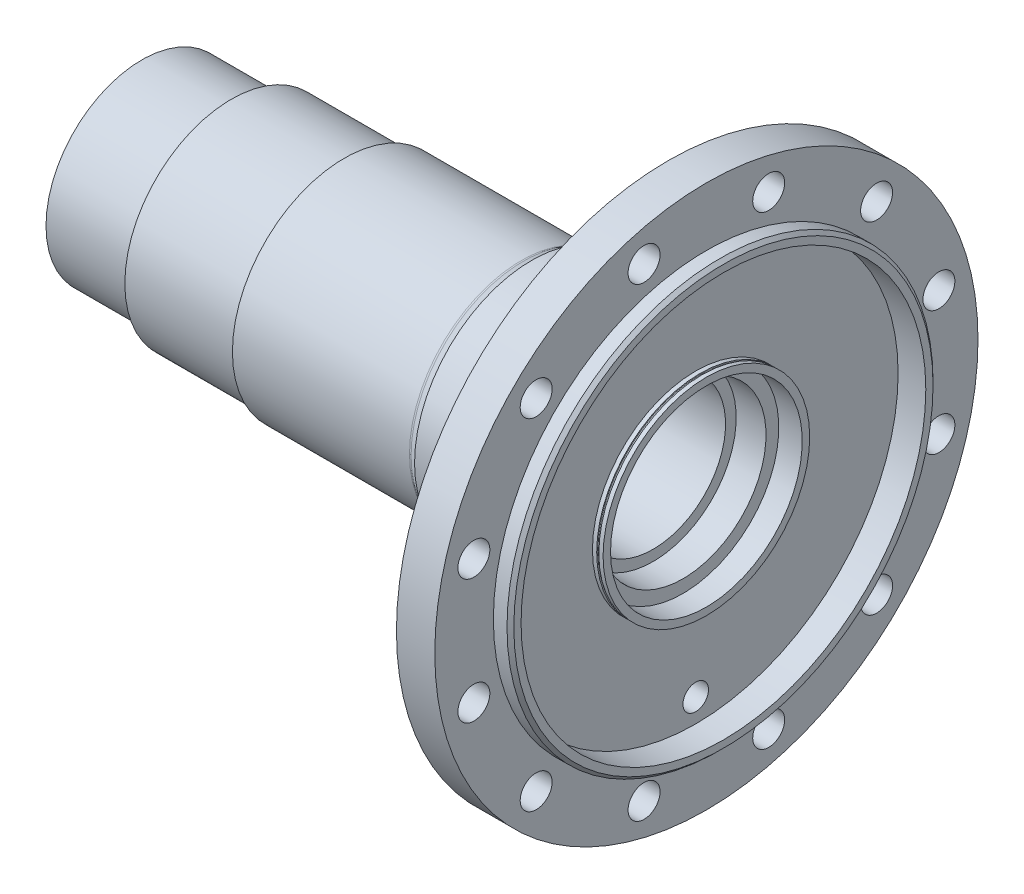
SolidWorks part; units mm, degrees
ref_plane "Спереди" through (0, 0, 0) normal (0, 0, 1) x (1, 0, 0)
ref_plane "Сверху" through (0, 0, 0) normal (0, 1, 0) x (1, 0, 0)
ref_plane "Справа" through (0, 0, 0) normal (1, 0, 0) x (0, 0, -1)
sketch "Эскиз1" plane through (0, 0, 0) normal (0, 0, 1) x (1, 0, 0)
  line L0 (0, 0) -> (273, 0)
  line L1 (0, 0) -> (0, 45)
  line L2 (0, 45) -> (42, 45)
  line L3 (42, 45) -> (42, 50)
  line L4 (42, 50) -> (95, 50)
  line L5 (95, 50) -> (95, 52.5)
  line L6 (95, 52.5) -> (178.134, 52.5)
  line L7 (179.134, 52.7679) -> (183, 55)
  line L8 (183, 55) -> (213, 55)
  line L9 (215, 57) -> (215, 60.7679)
  line L10 (215, 60.7679) -> (218, 62.5)
  line L11 (218, 62.5) -> (237, 62.5)
  line L12 (239, 64.5) -> (239, 100)
  line L13 (239, 100) -> (247, 100)
  line L14 (247, 100) -> (247, 127.5)
  line L15 (247, 127.5) -> (265, 127.5)
  line L16 (265, 127.5) -> (265, 100)
  line L17 (265, 100) -> (271.4, 100)
  line L18 (271.4, 100) -> (273, 98.4)
  line L19 (273, 98.4) -> (273, 0)
  arc A0 (178.134, 52.5) -> (179.134, 52.7679) centre (178.134, 54.5) ccw
  arc A1 (213, 55) -> (215, 57) centre (213, 57) ccw
  arc A2 (237, 62.5) -> (239, 64.5) centre (237, 64.5) ccw
revolve "Повернуть1" add sketch "Эскиз1" angle 360 about L0
sketch "Эскиз2" plane through (0, 0, 0) normal (0, 0, 1) x (1, 0, 0)
  line L0 (0, 0) -> (273, 0)
  line L1 (0, 0) -> (0, 31)
  line L2 (0, 31) -> (203.5, 31)
  line L3 (203.5, 31) -> (203.5, 34)
  line L4 (203.5, 34) -> (240, 34)
  line L5 (240, 34) -> (240, 39)
  line L6 (240, 39) -> (254, 39)
  line L7 (254, 39) -> (254, 45)
  line L8 (254, 45) -> (265, 45)
  line L9 (265, 45) -> (265, 95)
  line L10 (265, 95) -> (273, 95)
  line L11 (273, 95) -> (273, 0)
revolve "Вырез-Повернуть1" cut sketch "Эскиз2" angle 360 about L0
sketch "Эскиз3" plane through (0, 0, 0) normal (0, 0, 1) x (1, 0, 0)
  line L0 (0, 0) -> (273, 0) construction
  line L1 (260, 48.5) -> (262, 48.5)
  line L2 (262, 48.5) -> (262, 95)
  line L3 (262, 95) -> (260, 95)
  line L4 (260, 95) -> (260, 48.5)
revolve "Rear_recess_left" cut sketch "Эскиз3" angle 360 about L0
sketch "Эскиз4" plane through (0, 0, 0) normal (0, 0, 1) x (1, 0, 0)
  line L0 (0, 0) -> (273, 0) construction
  line L1 (263, 48) -> (263, 95)
  line L2 (263, 95) -> (262, 95)
  line L3 (262, 95) -> (262, 48)
  arc A0 (262, 48) -> (262.5, 47.5) centre (262.5, 48) ccw
  arc A1 (262.5, 47.5) -> (263, 48) centre (262.5, 48) ccw
revolve "Collar_groove_nominal" cut sketch "Эскиз4" angle 360 about L0
sketch "Эскиз5" plane through (0, 0, 0) normal (0, 0, 1) x (1, 0, 0)
  line L0 (0, 0) -> (273, 0) construction
  line L1 (263, 48.5) -> (265, 48.5)
  line L2 (265, 48.5) -> (265, 95)
  line L3 (265, 95) -> (263, 95)
  line L4 (263, 95) -> (263, 48.5)
revolve "Rear_recess_lip" cut sketch "Эскиз5" angle 360 about L0
sketch "Эскиз6" plane through (0, 0, 0) normal (1, 0, 0) x (0, 0, -1)
  circle A0 centre (109.1496, 29.2466) radius 7.5
extrude "Вырез-Вытянуть1" cut sketch "Эскиз6" along normal through all
sketch "Эскиз7" plane through (0, 0, 0) normal (1, 0, 0) x (0, 0, -1)
  circle A0 centre (79.9031, 79.9031) radius 7.5
extrude "Вырез-Вытянуть2" cut sketch "Эскиз7" along normal through all
sketch "Эскиз8" plane through (0, 0, 0) normal (1, 0, 0) x (0, 0, -1)
  circle A0 centre (29.2466, 109.1496) radius 7.5
extrude "Вырез-Вытянуть3" cut sketch "Эскиз8" along normal through all
sketch "Эскиз9" plane through (0, 0, 0) normal (1, 0, 0) x (0, 0, -1)
  circle A0 centre (-29.2466, 109.1496) radius 7.5
extrude "Вырез-Вытянуть4" cut sketch "Эскиз9" along normal through all
sketch "Эскиз10" plane through (0, 0, 0) normal (1, 0, 0) x (0, 0, -1)
  circle A0 centre (-79.9031, 79.9031) radius 7.5
extrude "Вырез-Вытянуть5" cut sketch "Эскиз10" along normal through all
sketch "Эскиз11" plane through (0, 0, 0) normal (1, 0, 0) x (0, 0, -1)
  circle A0 centre (-109.1496, 29.2466) radius 7.5
extrude "Вырез-Вытянуть6" cut sketch "Эскиз11" along normal through all
sketch "Эскиз12" plane through (0, 0, 0) normal (1, 0, 0) x (0, 0, -1)
  circle A0 centre (-109.1496, -29.2466) radius 7.5
extrude "Вырез-Вытянуть7" cut sketch "Эскиз12" along normal through all
sketch "Эскиз13" plane through (0, 0, 0) normal (1, 0, 0) x (0, 0, -1)
  circle A0 centre (-79.9031, -79.9031) radius 7.5
extrude "Вырез-Вытянуть8" cut sketch "Эскиз13" along normal through all
sketch "Эскиз14" plane through (0, 0, 0) normal (1, 0, 0) x (0, 0, -1)
  circle A0 centre (-29.2466, -109.1496) radius 7.5
extrude "Вырез-Вытянуть9" cut sketch "Эскиз14" along normal through all
sketch "Эскиз15" plane through (0, 0, 0) normal (1, 0, 0) x (0, 0, -1)
  circle A0 centre (29.2466, -109.1496) radius 7.5
extrude "Вырез-Вытянуть10" cut sketch "Эскиз15" along normal through all
sketch "Эскиз16" plane through (0, 0, 0) normal (1, 0, 0) x (0, 0, -1)
  circle A0 centre (79.9031, -79.9031) radius 7.5
extrude "Вырез-Вытянуть11" cut sketch "Эскиз16" along normal through all
sketch "Эскиз17" plane through (0, 0, 0) normal (1, 0, 0) x (0, 0, -1)
  circle A0 centre (109.1496, -29.2466) radius 7.5
extrude "Вырез-Вытянуть12" cut sketch "Эскиз17" along normal through all
sketch "Эскиз18" plane through (0, 0, 0) normal (1, 0, 0) x (0, 0, -1)
  circle A0 centre (0, -84) radius 6
extrude "Вырез-Вытянуть13" cut sketch "Эскиз18" along normal through all
